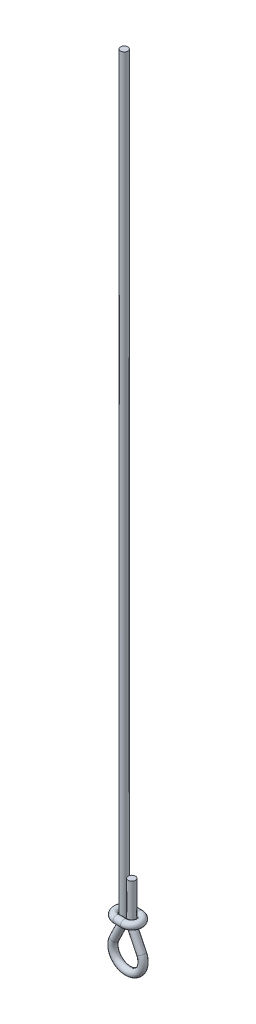
SolidWorks part; units mm, degrees
material "Silicon"
ref_plane "Front Plane" through (0, 0, 0) normal (0, 0, 1) x (1, 0, 0)
ref_plane "Top Plane" through (0, 0, 0) normal (0, 1, 0) x (1, 0, 0)
ref_plane "Right Plane" through (0, 0, 0) normal (1, 0, 0) x (0, 0, -1)
sketch "Sketch1" plane through (0, 0, 0) normal (0, 0, 1) x (1, 0, 0)
  line L0 (0, 150) -> (0, 0)
  line L1 (0, 0) -> (-1.9473, -4)
  line L2 (1.5, 0) -> (3.4473, -4)
  line L3 (1.5, 0) -> (1.5, 8)
  arc A0 (-1.9473, -4) -> (3.4473, -4) centre (0.75, -5.3132) ccw
  dimension "D1" = 3
  dimension "D2" = 4
  dimension "D3" = 150
  dimension "D4" = 1.5
  dimension "D5" = 8
sweep "Sweep1" add path "Sketch1" circular profile diameter 1.45 parameters "D3"=1.45
ref_plane "Plane1" through (0, 1, 0) normal (0, 1, 0) x (1, 0, 0)
sketch "Sketch18" plane through (0, 1, 0) normal (0, 1, 0) x (1, 0, 0)
  line L0 (0, 0) -> (1.5, 0) construction
  line L1 (0, 1.5) -> (1.5, 1.5)
  line L2 (0, -1.5) -> (1.5, -1.5)
  arc A0 (0, 1.5) -> (0, -1.5) centre (0, 0) ccw
  arc A1 (1.5, -1.5) -> (1.5, 1.5) centre (1.5, 0) ccw
  circle A2 centre (1.5, 0) radius 0.725 construction
  point P3 (0.75, 0)
  point P8 (0, 0)
  dimension "D1" = 1.5
sweep "Sweep2" add path "Sketch18" circular profile diameter 1.45 parameters "D3"=1.45
ref_plane "Plane2" through (0.75, 0, 0) normal (1, 0, 0) x (0, 0, -1)
ref_plane "Plane3" through (0, -7.5, 0) normal (0, 1, 0) x (1, 0, 0)
